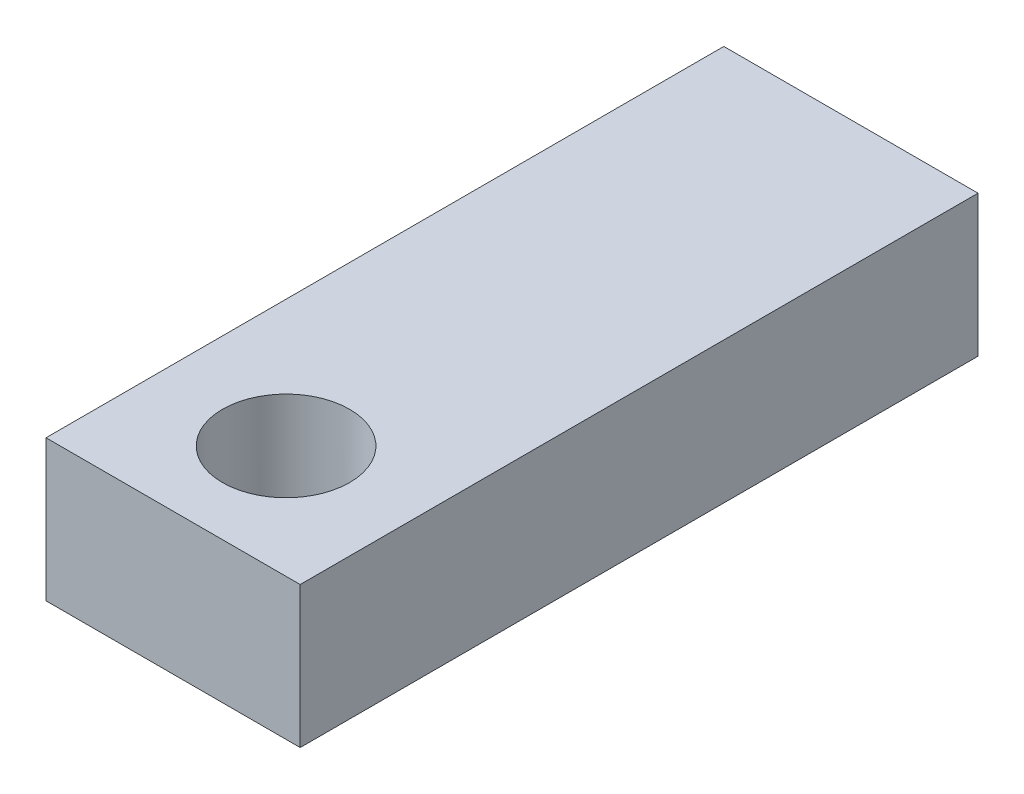
SolidWorks part; units mm, degrees
ref_plane "Alzado" through (0, 0, 0) normal (0, 0, 1) x (1, 0, 0)
ref_plane "Planta" through (0, 0, 0) normal (0, 1, 0) x (1, 0, 0)
ref_plane "Vista lateral" through (0, 0, 0) normal (1, 0, 0) x (0, 0, -1)
sketch "Croquis1" plane through (0, 0, 0) normal (0, 0, 1) x (1, 0, 0)
  line L1 (4.5, -2.5) -> (-4.5, -2.5)
  line L2 (4.5, -2.5) -> (4.5, 2.5)
  line L3 (4.5, 2.5) -> (-4.5, 2.5)
  line L4 (-4.5, -2.5) -> (-4.5, 2.5)
  line L5 (4.5, -2.5) -> (-4.5, 2.5) construction
  line L6 (4.5, 2.5) -> (-4.5, -2.5) construction
  point P0 (0, 0)
  dimension "D1" = 9
  dimension "D2" = 5
extrude "Saliente-Extruir1" add sketch "Croquis1" along normal blind 24
sketch "Croquis2" plane through (0, 0, 0) normal (0, 0, -1) x (-1, 0, 0)
  line L1 (3.75, -1.75) -> (-3.75, -1.75)
  line L2 (3.75, -1.75) -> (3.75, 1.75)
  line L3 (3.75, 1.75) -> (-3.75, 1.75)
  line L4 (-3.75, -1.75) -> (-3.75, 1.75)
  line L5 (3.75, -1.75) -> (-3.75, 1.75) construction
  line L6 (3.75, 1.75) -> (-3.75, -1.75) construction
  point P0 (0, 0)
  dimension "D1" = 7.5
  dimension "D2" = 3.5
extrude "Cortar-Extruir1" cut sketch "Croquis2" against normal blind 9
sketch "Croquis3" plane through (0, 2.5, 0) normal (0, 1, 0) x (1, 0, 0)
  line L1 (4.5, -12) -> (-4.3838, -12) construction
  line L2 (4.5, -24) -> (4.5, 0) construction
  line L3 (0, -24) -> (0, -20) construction
  line L4 (4.5, -24) -> (-4.5, -24) construction
  circle A1 centre (0, -20) radius 2.25
  point P1 (0, 0)
  dimension "D1" = 4
extrude "Cortar-Extruir2" cut sketch "Croquis3" against normal blind 9
